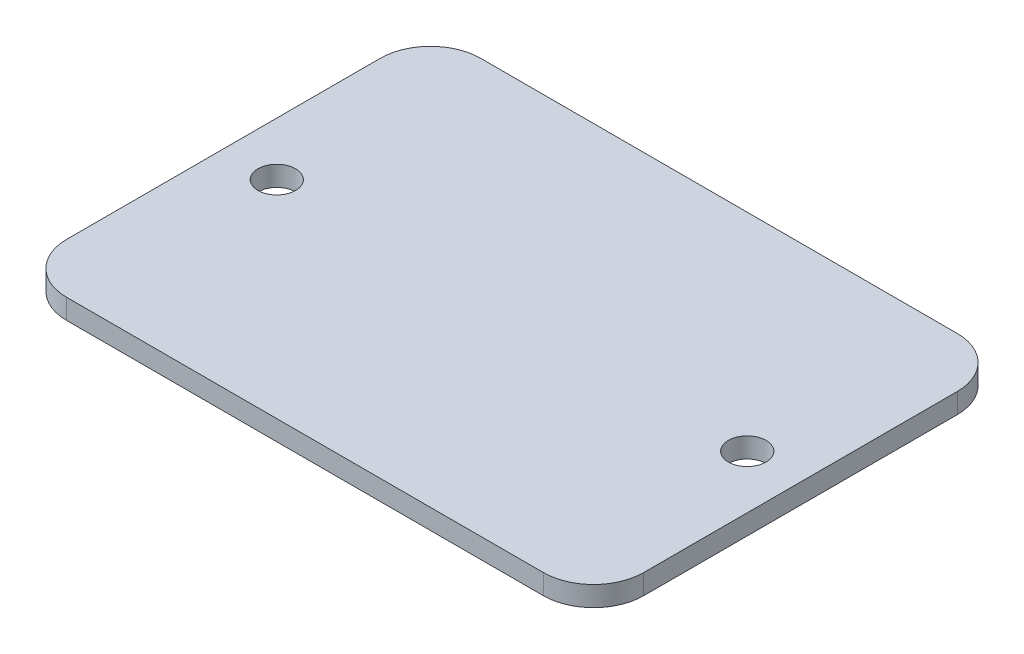
SolidWorks part; units mm, degrees
ref_plane "Front Plane" through (0, 0, 0) normal (0, 0, 1) x (1, 0, 0)
ref_plane "Top Plane" through (0, 0, 0) normal (0, 1, 0) x (1, 0, 0)
ref_plane "Right Plane" through (0, 0, 0) normal (1, 0, 0) x (0, 0, -1)
sketch "Sketch1" plane through (0, 0, 0) normal (0, 1, 0) x (1, 0, 0)
  line L0 (-23, 0) -> (23, 0) construction
  line L1 (-23, -16.5) -> (23, -16.5)
  line L2 (-23, -16.5) -> (-23, 16.5)
  line L3 (-23, 16.5) -> (23, 16.5)
  line L4 (23, -16.5) -> (23, 16.5)
  line L5 (-23, -16.5) -> (23, 16.5) construction
  line L6 (-23, 16.5) -> (23, -16.5) construction
  line L7 (0, 16.5) -> (0, -16.5) construction
  circle A0 centre (-18.75, 0) radius 1.5
  circle A1 centre (18.75, 0) radius 1.5
  point P0 (0, 0)
  dimension "D3" = 3
  dimension "D1" = 46
  dimension "D2" = 33
  dimension "D4" = 37.5
extrude "Boss-Extrude1" add sketch "Sketch1" along normal blind 1.6
fillet "Fillet1" radius 4 4 edges at (-23, 0.8, -16.5) (23, 0.8, -16.5) (23, 0.8, 16.5) (-23, 0.8, 16.5)
